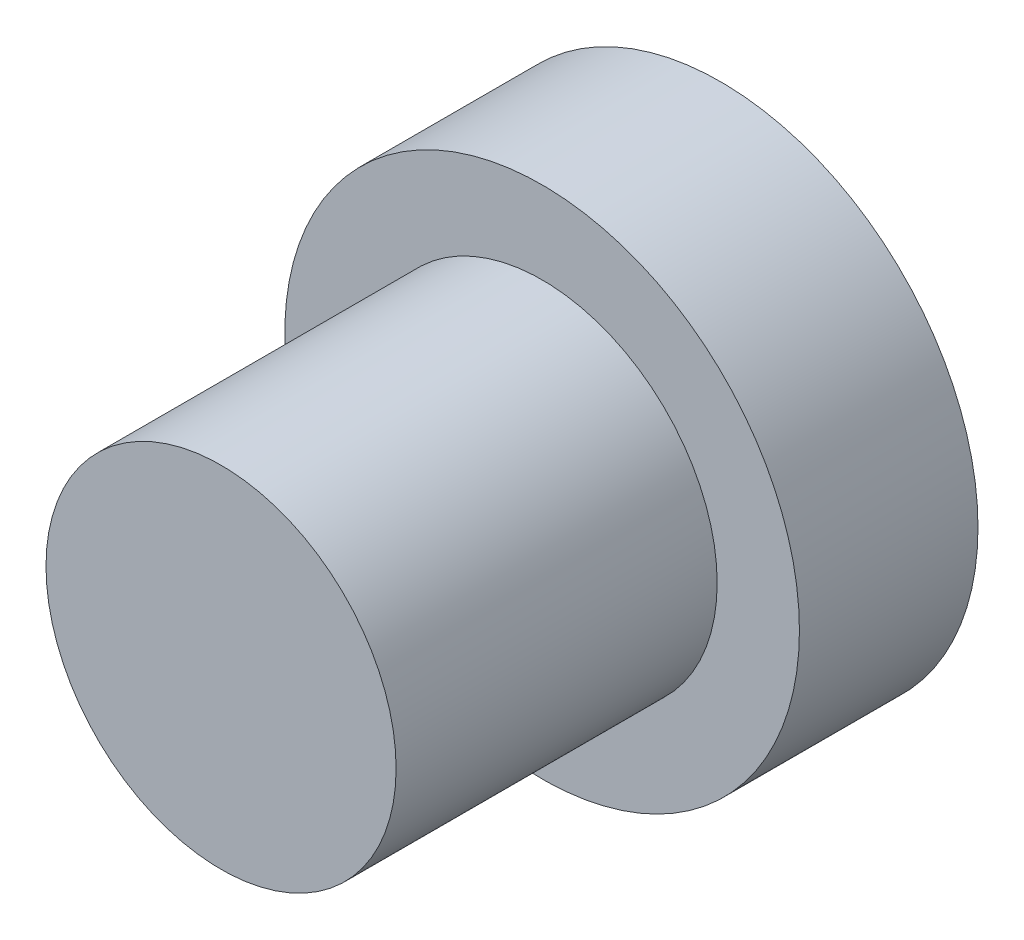
SolidWorks part; units mm, degrees
ref_plane "Front Plane" through (0, 0, 0) normal (0, 0, 1) x (1, 0, 0)
ref_plane "Top Plane" through (0, 0, 0) normal (0, 1, 0) x (1, 0, 0)
ref_plane "Right Plane" through (0, 0, 0) normal (1, 0, 0) x (0, 0, -1)
sketch "Sketch1" plane through (0, 0, 0) normal (0, 0, 1) x (1, 0, 0)
  circle A0 centre (0, 0) radius 7.35
  dimension "D1" = 14.7
extrude "Boss-Extrude1" add sketch "Sketch1" along normal blind 5.1
sketch "Sketch2" plane through (0, 0, 5.1) normal (0, 0, 1) x (1, 0, 0)
  circle A0 centre (0, 0) radius 5
  dimension "D1" = 10
extrude "Boss-Extrude2" add sketch "Sketch2" along normal blind 9.17
